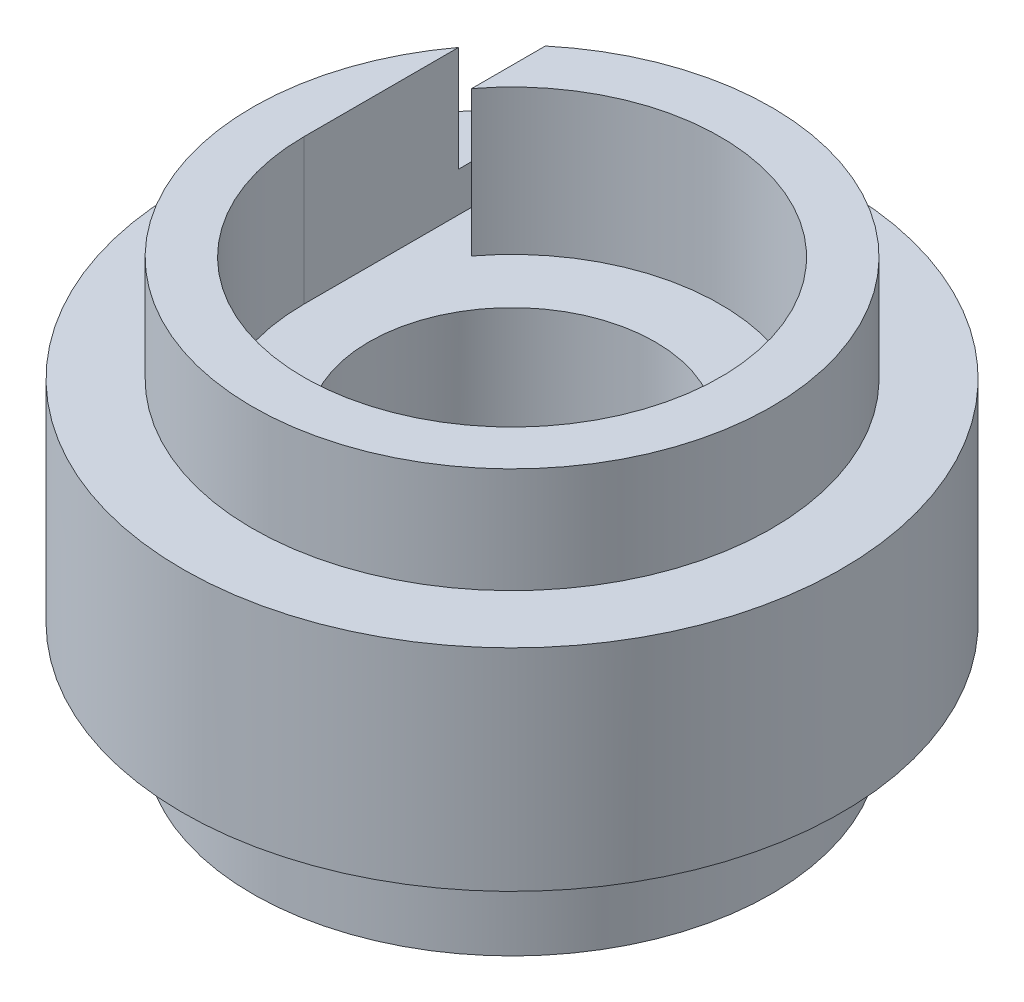
SolidWorks part; units mm, degrees
ref_plane "Front Plane" through (0, 0, 0) normal (0, 0, 1) x (1, 0, 0)
ref_plane "Top Plane" through (0, 0, 0) normal (0, 1, 0) x (1, 0, 0)
ref_plane "Right Plane" through (0, 0, 0) normal (1, 0, 0) x (0, 0, -1)
sketch "Sketch1" plane through (0, 0, 0) normal (0, 1, 0) x (1, 0, 0)
  circle A0 centre (0, 0) radius 31.75
  circle A1 centre (0, 0) radius 13.7886
  dimension "D1" = 63.5
extrude "Boss-Extrude1" add sketch "Sketch1" along normal mid plane 40.64
sketch "Sketch2" plane through (0, 20.32, 0) normal (0, 1, 0) x (1, 0, 0)
  line L0 (-20.066, 0) -> (-20.066, 24.6052)
  line L1 (-16.002, 12.107) -> (-16.002, 27.4226)
  arc A0 (-20.066, 0) -> (-16.002, 12.107) centre (0, 0) ccw
  circle A1 centre (0, 0) radius 31.75 construction
  arc A2 (-16.002, 27.4226) -> (-20.066, 24.6052) centre (0, 0) ccw
  dimension "D1" = 4.064
extrude "Cut-Extrude1" cut sketch "Sketch2" against normal blind 13.97
sketch "Sketch13" plane through (0, 20.32, 0) normal (0, 1, 0) x (1, 0, 0)
  circle A1 centre (0, 0) radius 25
  circle A2 centre (0, 0) radius 31.75
  arc A3 (-20.066, 24.6052) -> (-16.002, 27.4226) centre (0, 0) ccw construction
extrude "Cut-Extrude2" cut sketch "Sketch13" against normal blind 10.16
sketch "Sketch5" plane through (0, 0, 0) normal (0, 1, 0) x (1, 0, 0)
  line L0 (0, -39.3443) -> (0, 40.2571) construction
  line L1 (0, -22.352) -> (0, 22.352) construction
sketch "Sketch9" plane through (0, 0, 0) normal (0, 0, 1) x (1, 0, 0)
  line L0 (0, -22.352) -> (0, 22.352) construction
  line L1 (-20.066, 3.81) -> (-14.478, 3.81)
  line L2 (-20.066, 3.81) -> (-20.066, 0)
  line L3 (-20.066, 0) -> (-14.478, 0)
  line L4 (-14.478, 3.81) -> (-14.478, 0)
  point P5 (-14.478, 1.905)
  dimension "D1" = 3.81
  dimension "D2" = 14.478
sketch "Sketch12" plane through (0, 6.35, 0) normal (0, 1, 0) x (1, 0, 0)
  circle A0 centre (0, 0) radius 13.7886
  circle A1 centre (0, 0) radius 13.7886 construction
curve "Helix/Spiral2" pitch 3.302 height 2.9619 turns 0.897
pattern_circular "CirPattern1" count 2 over 360 about axis through (0, 0, 0) along (0, 0, 1) of "Cut-Extrude2", "Cut-Extrude1"
